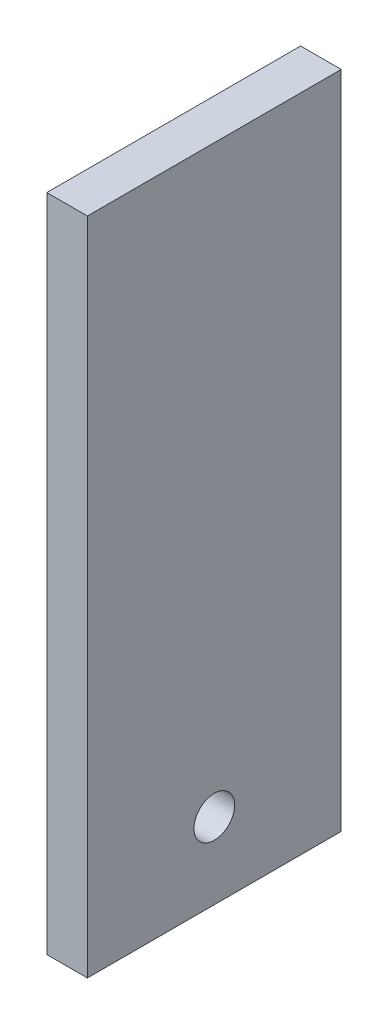
SolidWorks part; units mm, degrees
ref_plane "Front Plane" through (0, 0, 0) normal (0, 0, 1) x (1, 0, 0)
ref_plane "Top Plane" through (0, 0, 0) normal (0, 1, 0) x (1, 0, 0)
ref_plane "Right Plane" through (0, 0, 0) normal (1, 0, 0) x (0, 0, -1)
sketch "Sketch1" plane through (0, 0, 0) normal (1, 0, 0) x (0, 0, -1)
  line L1 (0, 0) -> (50, 0)
  line L2 (0, 0) -> (0, 130)
  line L3 (0, 130) -> (50, 130)
  line L4 (50, 0) -> (50, 130)
  dimension "D1" = 50
  dimension "D2" = 130
extrude "Boss-Extrude1" add sketch "Sketch1" along normal blind 8 contours L3 L4 L1 L2
sketch "Sketch2" plane through (0, 0, 0) normal (1, 0, 0) x (0, 0, -1)
  line L0 (0, 0) -> (0, 130) construction
  line L1 (0, 0) -> (50, 0) construction
  circle A0 centre (25, 15) radius 4
  dimension "D1" = 25
  dimension "D2" = 15
extrude "Cut-Extrude3" cut sketch "Sketch2" along normal up to surface (8 mm away) up to face at (8, 65, -25)
